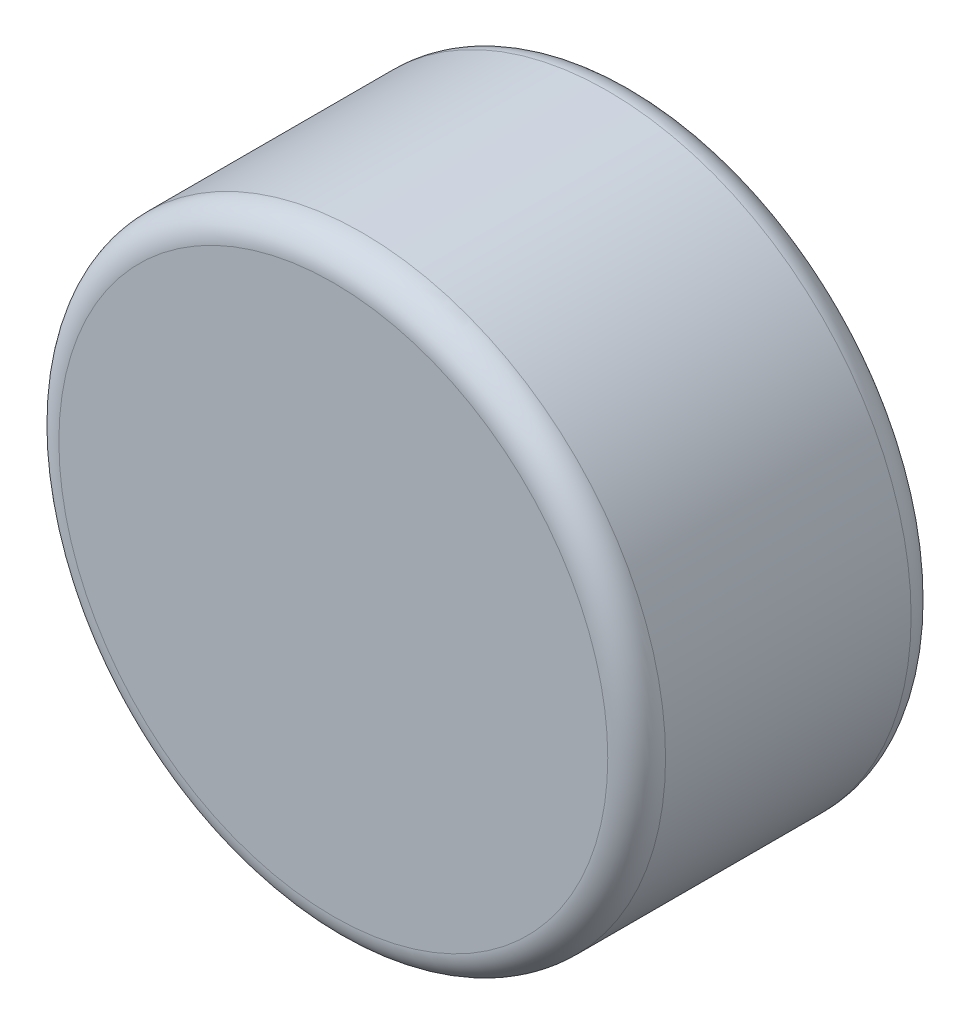
SolidWorks part; units mm, degrees
ref_plane "Front Plane" through (0, 0, 0) normal (0, 0, 1) x (1, 0, 0)
ref_plane "Top Plane" through (0, 0, 0) normal (0, 1, 0) x (1, 0, 0)
ref_plane "Right Plane" through (0, 0, 0) normal (1, 0, 0) x (0, 0, -1)
sketch "Sketch1" plane through (0, 0, 0) normal (0, 0, 1) x (1, 0, 0)
  circle A0 centre (0, 0) radius 3.15
  dimension "D1" = 6.3
extrude "Boss-Extrude1" add sketch "Sketch1" along normal blind 3.15
fillet "Fillet1" radius 0.3 2 edges at (3.15, 0, 0) (3.15, 0, 3.15)
